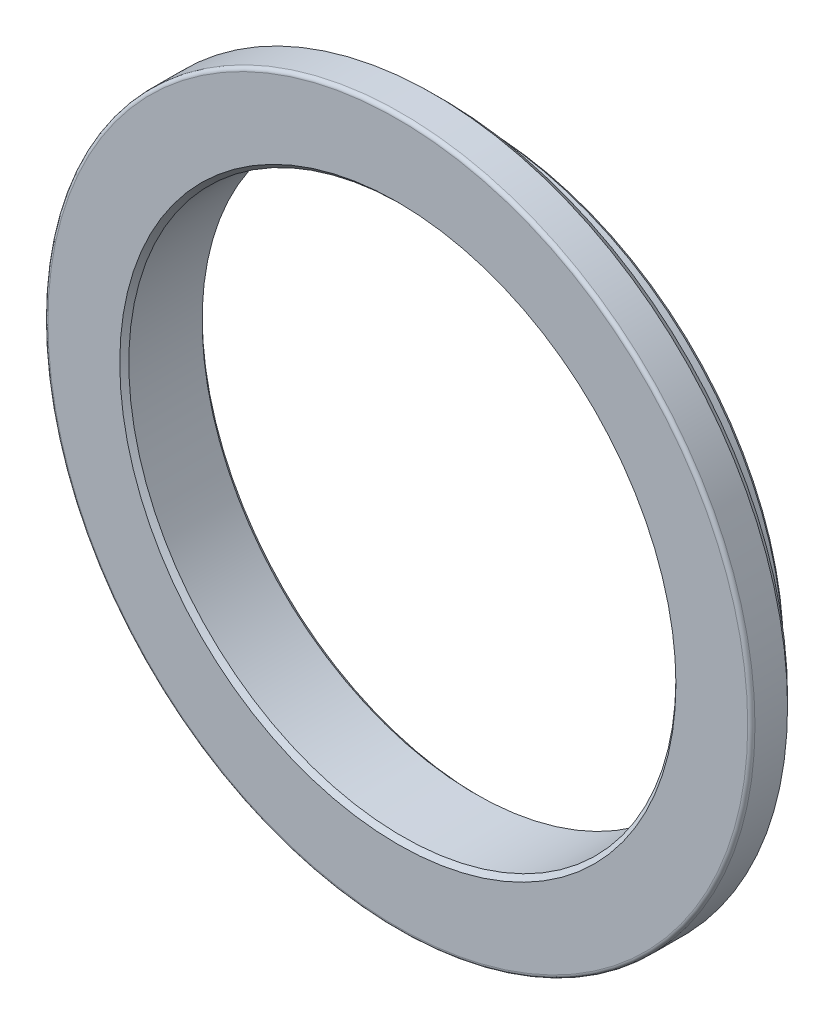
SolidWorks part; units mm, degrees
material "PB01 (C90710) Bronze"
ref_plane "Front Plane" through (0, 0, 0) normal (0, 0, 1) x (1, 0, 0)
ref_plane "Top Plane" through (0, 0, 0) normal (0, 1, 0) x (1, 0, 0)
ref_plane "Right Plane" through (0, 0, 0) normal (1, 0, 0) x (0, 0, -1)
sketch "Sketch1" plane through (0, 0, 0) normal (1, 0, 0) x (0, 0, -1)
  line L0 (0, 0) -> (41.4438, 0) construction
  line L1 (0, 30.725) -> (0.5, 30.225)
  line L2 (0.4, 39.06) -> (4, 39.06)
  line L3 (0, 38.66) -> (0, 30.725)
  line L4 (0.5, 30.225) -> (8.6, 30.225)
  line L5 (5, 38.06) -> (5, 34.4)
  line L6 (9.1, 30.725) -> (8.6, 30.225)
  line L8 (4, 39.06) -> (5, 38.06)
  line L9 (5.4, 34) -> (8.6, 34)
  line L10 (9.1, 33.5) -> (9.1, 30.725)
  line L11 (8.6, 34) -> (9.1, 33.5)
  arc A0 (5.4, 34) -> (5, 34.4) centre (5.4, 34.4) cw
  arc A1 (0, 38.66) -> (0.4, 39.06) centre (0.4, 38.66) cw
  point P5 (0, 30.225)
  point P6 (5, 39.06)
  point P16 (9.1, 34)
  point P17 (9.1, 30.225)
  dimension "D7" = 0.4
  dimension "D8" = 0.4
  dimension "D1" = 60.45
  dimension "D2" = 78.12
  dimension "D3" = 5
  dimension "D4" = 68
  dimension "D5" = 9.1
revolve "Revolve1" add sketch "Sketch1" angle 360 about L0
